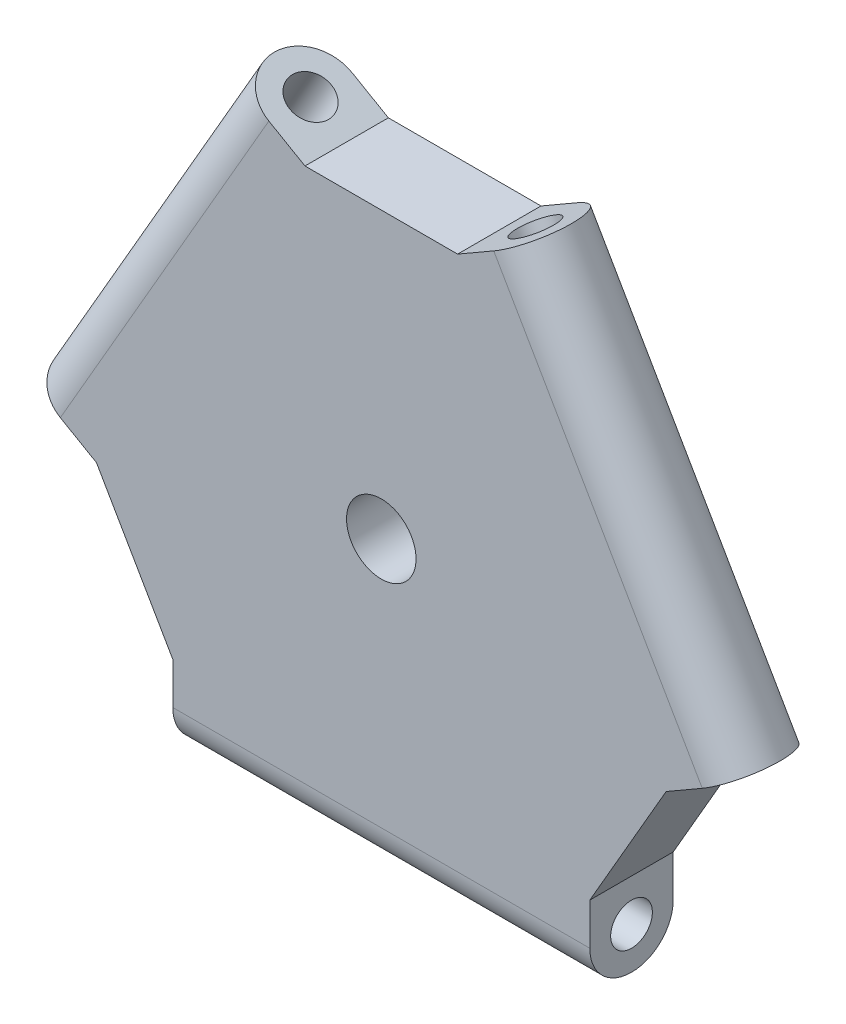
SolidWorks part; units mm, degrees
ref_plane "前视基准面" through (0, 0, 0) normal (0, 0, 1) x (1, 0, 0)
ref_plane "上视基准面" through (0, 0, 0) normal (0, 1, 0) x (1, 0, 0)
ref_plane "右视基准面" through (0, 0, 0) normal (1, 0, 0) x (0, 0, -1)
sketch "草图1" plane through (0, 0, 0) normal (0, 0, 1) x (1, 0, 0)
  line L1 (0, 60) -> (-51.9615, -30)
  line L2 (-51.9615, -30) -> (51.9615, -30)
  line L3 (51.9615, -30) -> (0, 60)
  circle A0 centre (0, 0) radius 30 construction
  dimension "D1" = 30
extrude "凸台-拉伸1" add sketch "草图1" along normal blind 12
sketch "草图2" plane through (0, 0, 0) normal (1, 0, 0) x (0, 0, -1)
  line L0 (-6, 60) -> (-6, -58.4332) construction
  line L1 (-12, 60) -> (0, 60) construction
  line L3 (-12, -42) -> (0, -42)
  line L4 (-12, -42) -> (-12, -30)
  line L5 (-12, -30) -> (0, -30)
  line L6 (0, -42) -> (0, -30)
  line L7 (-12, -42) -> (0, -30) construction
  line L8 (-12, -30) -> (0, -42) construction
  circle A0 centre (-6, -36) radius 6
  point P4 (-6, -36)
  dimension "D1" = 12
extrude "凸台-拉伸2" add sketch "草图2" along normal mid plane 60 contours A0 | A0 L6 L5 | A0 L5 L4
sketch "草图3" plane through (30, 0, 0) normal (1, 0, 0) x (0, 0, -1)
  circle A0 centre (-6, -36) radius 3
  dimension "D1" = 6
extrude "切除-拉伸1" cut sketch "草图3" against normal through all
sketch "草图5" plane through (0, 0, 0) normal (0, 0, -1) x (-1, 0, 0)
  circle A0 centre (0, 0) radius 5
  dimension "D1" = 10
extrude "切除-拉伸2" cut sketch "草图5" against normal through all
sketch "草图6" plane through (0, 0, 0) normal (0, 0, -1) x (-1, 0, 0)
  line L0 (-30, -30) -> (-51.9615, -30)
  line L1 (-51.9615, -30) -> (-40.9808, -10.9808)
  line L2 (-51.9615, -30) -> (0, 60) construction
  line L3 (-40.9808, -10.9808) -> (-30, -30)
  line L4 (10.9808, 40.9808) -> (-10.9808, 40.9808)
  line L5 (-10.9808, 40.9808) -> (0, 60)
  line L6 (0, 60) -> (10.9808, 40.9808)
  line L7 (30, -30) -> (40.9808, -10.9808)
  line L8 (40.9808, -10.9808) -> (51.9615, -30)
  line L9 (51.9615, -30) -> (30, -30)
  point P15 (0, 0)
  dimension "D1" = 60
  dimension "D2" = 3
extrude "切除-拉伸3" cut sketch "草图6" against normal through all
pattern_circular "阵列(圆周)2" count 3 over 360 about axis through (0, 0, 0) along (0, 0, 1) of "凸台-拉伸2"
sketch "草图7" plane through (15, -25.9808, 0) normal (0.5, -0.866, 0) x (0.866, 0.5, 0)
  circle A0 centre (36, 6) radius 3
  dimension "D1" = 6
extrude "切除-拉伸4" cut sketch "草图7" against normal through all
sketch "草图8" plane through (15, 25.9808, 0) normal (0.5, 0.866, 0) x (0.866, -0.5, 0)
  circle A0 centre (-36, -6) radius 3
  dimension "D1" = 6
extrude "切除-拉伸5" cut sketch "草图8" against normal through all
